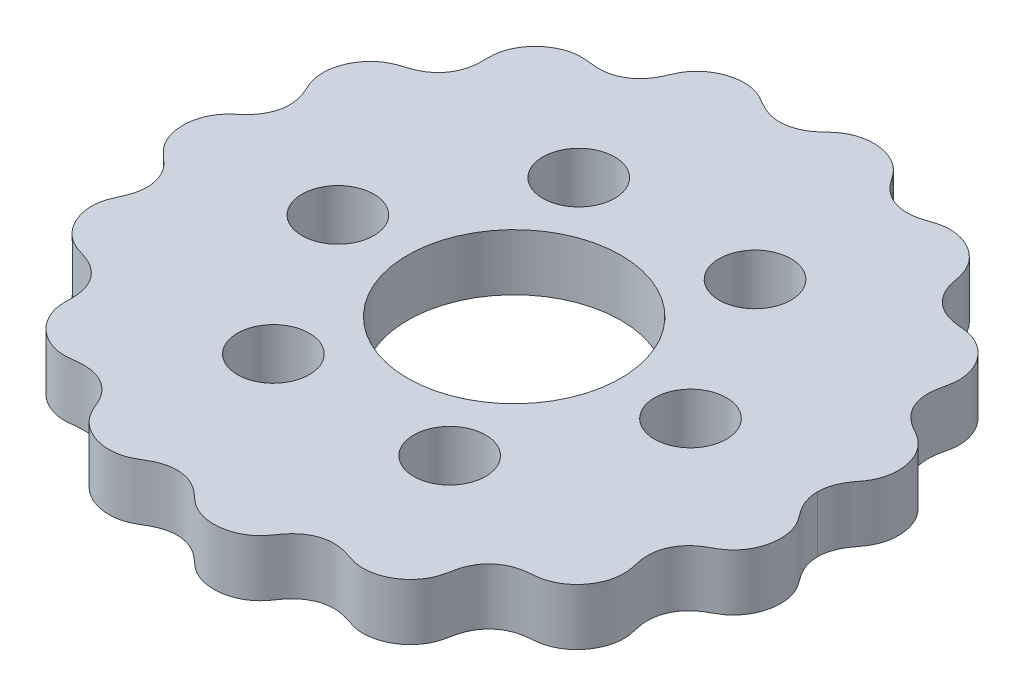
SolidWorks part; units mm, degrees
ref_plane "Alzado" through (0, 0, 0) normal (0, 0, 1) x (1, 0, 0)
ref_plane "Planta" through (0, 0, 0) normal (0, 1, 0) x (1, 0, 0)
ref_plane "Vista lateral" through (0, 0, 0) normal (1, 0, 0) x (0, 0, -1)
sketch "Croquis1" plane through (0, 0, 0) normal (0, 1, 0) x (1, 0, 0)
  line L1 (-23.5, 0) -> (21.5, 0) construction
  circle A8 centre (0, 0) radius 12.5 construction
  circle A9 centre (12.5, 0) radius 2.55
  circle A10 centre (6.25, -10.8253) radius 2.55
  circle A11 centre (-6.25, -10.8253) radius 2.55
  circle A12 centre (-12.5, 0) radius 2.55
  circle A13 centre (-6.25, 10.8253) radius 2.55
  circle A14 centre (6.25, 10.8253) radius 2.55
  circle A15 centre (0, 0) radius 7.56
  spline S0 degree 4 poles (22.3938, 6.206) (22.5098, 6.0505) (22.7166, 5.7207) (22.9456, 5.1865) (23.0698, 4.5223) (23.0708, 3.9491) (22.995, 3.4431) (22.8861, 3.0677) (22.7402, 2.7346) (22.5701, 2.4451) (22.4166, 2.2248) (22.255, 2.0106) (22.0968, 1.7938) (21.9608, 1.5854) (21.8481, 1.3858) (21.7364, 1.1545) (21.6505, 0.933) (21.5836, 0.7054) (21.5367, 0.4716) (21.5147, 0.3126) (21.5037, 0.1561) (21.4997, 0.0354) (21.4998, -0.0402) (21.5033, -0.1416) (21.5104, -0.2506) (21.521, -0.3535) (21.5352, -0.4522) (21.5572, -0.575) (21.5906, -0.7229) (21.6393, -0.8925) (21.7079, -1.082) (21.7887, -1.2667) (21.8884, -1.4605) (22.0086, -1.6616) (22.1498, -1.8685) (22.3094, -2.0824) (22.4687, -2.2964) (22.6163, -2.5189) (22.7773, -2.8114) (22.9505, -3.2395) (23.0755, -3.8173) (23.0785, -4.5347) (22.9117, -5.2906) (22.61, -5.9374) (22.2185, -6.4567) (21.7772, -6.8519) (21.3209, -7.1251) (20.8, -7.4026) (20.2753, -7.7948) (19.8063, -8.3446) (19.475, -9.0614) (19.3598, -9.7832) (19.4098, -10.4522) (19.5346, -10.9747) (19.6222, -11.3739) (19.6633, -11.7809) (19.6552, -12.251) (19.5391, -12.8416) (19.2523, -13.5076) (18.7937, -14.1364) (18.2622, -14.6034) (17.7101, -14.9167) (17.1699, -15.1) (16.67, -15.1754) (16.1916, -15.2048) (15.7411, -15.2785) (15.3268, -15.3998) (14.9543, -15.5661) (14.5264, -15.8332) (14.0827, -16.2428) (13.7242, -16.7761) (13.514, -17.344) (13.4123, -17.8049) (13.3351, -18.2081) (13.2359, -18.6074) (13.025, -19.1081) (12.6416, -19.6627) (12.1028, -20.1652) (11.4122, -20.5639) (10.7076, -20.7793) (10.0356, -20.834) (9.4966, -20.7664) (9.1011, -20.6526) (8.7134, -20.5178) (8.2633, -20.3754) (7.6664, -20.2735) (7.0253, -20.3174) (6.4487, -20.4968) (6.0035, -20.7338) (5.6732, -20.9733) (5.361, -21.2715) (5.0719, -21.6247) (4.8073, -22.0244) (4.4921, -22.4196) (4.0632, -22.7958) (3.5158, -23.1172) (2.8456, -23.344) (2.0718, -23.4267) (1.3515, -23.3422) (0.7822, -23.1473) (0.3707, -22.9196) (0.0947, -22.7199) (-0.1125, -22.543) (-0.3613, -22.3108) (-0.71, -21.9972) (-1.2072, -21.6575) (-1.8903, -21.3967) (-2.6764, -21.325) (-3.3872, -21.4564) (-3.9891, -21.7146) (-4.49, -22.027) (-4.9546, -22.2856) (-5.5176, -22.4702) (-6.163, -22.5495) (-6.8743, -22.4875) (-7.6119, -22.2539) (-8.2323, -21.8928) (-8.7188, -21.4502) (-9.0744, -20.9697) (-9.3045, -20.4864) (-9.5278, -19.9281) (-9.8701, -19.3468) (-10.3865, -18.8074) (-11.0945, -18.3987) (-11.8197, -18.2212) (-12.4943, -18.2154) (-13.0895, -18.3011) (-13.623, -18.3435) (-14.217, -18.2758) (-14.8436, -18.0758) (-15.4665, -17.719) (-16.0376, -17.197) (-16.447, -16.612) (-16.701, -16.0135) (-16.8226, -15.4336) (-16.8309, -14.902) (-16.8108, -14.312) (-16.8881, -13.6616) (-17.1298, -12.9803) (-17.5849, -12.3353) (-18.1524, -11.8742) (-18.6951, -11.6135) (-19.1411, -11.4683) (-19.4666, -11.3689) (-19.7233, -11.2779) (-20.0342, -11.1388) (-20.4373, -10.8962) (-20.8907, -10.5007) (-21.3241, -9.9191) (-21.6393, -9.2077) (-21.778, -8.5138) (-21.7733, -7.8791) (-21.6621, -7.3195) (-21.4771, -6.849) (-21.2186, -6.3289) (-21.0011, -5.7035) (-20.9214, -4.968) (-21.0454, -4.2657) (-21.2856, -3.7121) (-21.5436, -3.3243) (-21.7592, -3.0674) (-21.974, -2.8515) (-22.1775, -2.6683) (-22.3844, -2.489) (-22.5845, -2.3019) (-22.7693, -2.0995) (-22.9352, -1.8813) (-23.0967, -1.6229) (-23.2446, -1.3222) (-23.3437, -1.0477) (-23.4069, -0.8089) (-23.4413, -0.6387) (-23.4581, -0.5412) (-23.4757, -0.42) (-23.4911, -0.2795) (-23.5008, -0.0674) (-23.501, 0.0617) (-23.4905, 0.2958) (-23.4696, 0.4722) (-23.4384, 0.6634) (-23.3968, 0.8485) (-23.3447, 1.0319) (-23.2823, 1.2119) (-23.2033, 1.4023) (-23.1053, 1.6016) (-22.952, 1.8603) (-22.7243, 2.166) (-22.4073, 2.4773) (-22.0362, 2.7842) (-21.7134, 3.1099) (-21.3864, 3.5349) (-21.0986, 4.0919) (-20.9508, 4.7107) (-20.9589, 5.3479) (-21.0451, 5.768) (-21.1059, 5.9731) (-21.1402, 6.0744) knots 0 0 0 0 0 0.008384 0.016767 0.0249 0.028966 0.033032 0.038829 0.041728 0.044627 0.047525 0.050424 0.053322 0.056221 0.05827 0.060319 0.064418 0.066467 0.068516 0.070566 0.07159 0.072615 0.073703 0.074791 0.075879 0.076967 0.078055 0.079143 0.081319 0.083495 0.085672 0.087848 0.090024 0.092906 0.095787 0.098669 0.101551 0.104433 0.107315 0.113078 0.12144 0.129802 0.138039 0.146276 0.152005 0.157733 0.163462 0.169191 0.177517 0.185843 0.194348 0.202854 0.208734 0.214615 0.217555 0.220495 0.226376 0.23487 0.243365 0.251552 0.25974 0.265182 0.270624 0.276066 0.281508 0.285899 0.29029 0.294681 0.299071 0.307626 0.316181 0.322096 0.325053 0.328011 0.333925 0.33984 0.348384 0.356927 0.365471 0.374015 0.37993 0.385844 0.388802 0.391759 0.397674 0.406229 0.414784 0.419174 0.423565 0.427956 0.432347 0.437789 0.443231 0.448673 0.454115 0.462303 0.47049 0.478985 0.487479 0.49336 0.4963 0.49924 0.502181 0.505121 0.511001 0.519507 0.528012 0.536338 0.544664 0.550393 0.556122 0.56185 0.567579 0.575816 0.584053 0.592415 0.600777 0.60654 0.612304 0.618068 0.623831 0.632536 0.64124 0.649944 0.658649 0.664412 0.670176 0.67594 0.681703 0.690065 0.698427 0.706664 0.714901 0.72063 0.726358 0.732087 0.737816 0.746142 0.754468 0.762973 0.771479 0.777359 0.780299 0.78324 0.78618 0.78912 0.795001 0.803495 0.81199 0.820177 0.828365 0.833807 0.839249 0.844691 0.850133 0.858915 0.867696 0.876251 0.880529 0.884806 0.887763 0.890721 0.893678 0.896636 0.899593 0.90255 0.905508 0.908465 0.912737 0.917009 0.918077 0.919145 0.920213 0.921281 0.923416 0.925552 0.927609 0.929666 0.931723 0.93378 0.935836 0.937893 0.93995 0.942007 0.944741 0.947474 0.952942 0.95841 0.963877 0.968289 0.972701 0.981525 0.990762 0.995381 1 1 1 1 1 construction
  spline S1 degree 4 poles (21.5, 0) (21.5, -0.0215) (21.5006, -0.0644) (21.5033, -0.1416) (21.5104, -0.2506) (21.521, -0.3535) (21.5352, -0.4522) (21.5572, -0.575) (21.5906, -0.7229) (21.6393, -0.8925) (21.7079, -1.082) (21.7887, -1.2667) (21.8884, -1.4605) (22.0086, -1.6616) (22.1498, -1.8685) (22.3094, -2.0824) (22.4687, -2.2964) (22.6163, -2.5189) (22.7773, -2.8114) (22.9505, -3.2395) (23.0755, -3.8173) (23.0785, -4.5347) (22.9117, -5.2906) (22.61, -5.9374) (22.2185, -6.4567) (21.7772, -6.8519) (21.3209, -7.1251) (20.8, -7.4026) (20.2753, -7.7948) (19.8063, -8.3446) (19.475, -9.0614) (19.3598, -9.7832) (19.4098, -10.4522) (19.5346, -10.9747) (19.6222, -11.3739) (19.6633, -11.7809) (19.6552, -12.251) (19.5391, -12.8416) (19.2523, -13.5076) (18.7937, -14.1364) (18.2622, -14.6034) (17.7101, -14.9167) (17.1699, -15.1) (16.67, -15.1754) (16.1916, -15.2048) (15.7411, -15.2785) (15.3268, -15.3998) (14.9543, -15.5661) (14.5264, -15.8332) (14.0827, -16.2428) (13.7242, -16.7761) (13.514, -17.344) (13.4123, -17.8049) (13.3351, -18.2081) (13.2359, -18.6074) (13.025, -19.1081) (12.6416, -19.6627) (12.1028, -20.1652) (11.4122, -20.5639) (10.7076, -20.7793) (10.0356, -20.834) (9.4966, -20.7664) (9.1011, -20.6526) (8.7134, -20.5178) (8.2633, -20.3754) (7.6664, -20.2735) (7.0253, -20.3174) (6.4487, -20.4968) (6.0035, -20.7338) (5.6732, -20.9733) (5.361, -21.2715) (5.0719, -21.6247) (4.8073, -22.0244) (4.4921, -22.4196) (4.0632, -22.7958) (3.5158, -23.1172) (2.8456, -23.344) (2.0718, -23.4267) (1.3515, -23.3422) (0.7822, -23.1473) (0.3707, -22.9196) (0.0947, -22.7199) (-0.1125, -22.543) (-0.3613, -22.3108) (-0.71, -21.9972) (-1.2072, -21.6575) (-1.8903, -21.3967) (-2.6764, -21.325) (-3.3872, -21.4564) (-3.9891, -21.7146) (-4.49, -22.027) (-4.9546, -22.2856) (-5.5176, -22.4702) (-6.163, -22.5495) (-6.8743, -22.4875) (-7.6119, -22.2539) (-8.2323, -21.8928) (-8.7188, -21.4502) (-9.0744, -20.9697) (-9.3045, -20.4864) (-9.5278, -19.9281) (-9.8701, -19.3468) (-10.3865, -18.8074) (-11.0945, -18.3987) (-11.8197, -18.2212) (-12.4943, -18.2154) (-13.0895, -18.3011) (-13.623, -18.3435) (-14.217, -18.2758) (-14.8436, -18.0758) (-15.4665, -17.719) (-16.0376, -17.197) (-16.447, -16.612) (-16.701, -16.0135) (-16.8226, -15.4336) (-16.8309, -14.902) (-16.8108, -14.312) (-16.8881, -13.6616) (-17.1298, -12.9803) (-17.5849, -12.3353) (-18.1524, -11.8742) (-18.6951, -11.6135) (-19.1411, -11.4683) (-19.4666, -11.3689) (-19.7233, -11.2779) (-20.0342, -11.1388) (-20.4373, -10.8962) (-20.8907, -10.5007) (-21.3241, -9.9191) (-21.6393, -9.2077) (-21.778, -8.5138) (-21.7733, -7.8791) (-21.6621, -7.3195) (-21.4771, -6.849) (-21.2186, -6.3289) (-21.0011, -5.7035) (-20.9214, -4.968) (-21.0454, -4.2657) (-21.2856, -3.7121) (-21.5436, -3.3243) (-21.7592, -3.0674) (-21.974, -2.8515) (-22.1775, -2.6683) (-22.3844, -2.489) (-22.5845, -2.3019) (-22.7693, -2.0995) (-22.9352, -1.8813) (-23.0967, -1.6229) (-23.2446, -1.3222) (-23.3437, -1.0477) (-23.4069, -0.8089) (-23.4413, -0.6387) (-23.4581, -0.5412) (-23.4757, -0.42) (-23.4911, -0.2795) (-23.4981, -0.1264) (-23.5, -0.0422) (-23.5, 0) knots 0.072615 0.072615 0.072615 0.072615 0.072615 0.073703 0.074791 0.075879 0.076967 0.078055 0.079143 0.081319 0.083495 0.085672 0.087848 0.090024 0.092906 0.095787 0.098669 0.101551 0.104433 0.107315 0.113078 0.12144 0.129802 0.138039 0.146276 0.152005 0.157733 0.163462 0.169191 0.177517 0.185843 0.194348 0.202854 0.208734 0.214615 0.217555 0.220495 0.226376 0.23487 0.243365 0.251552 0.25974 0.265182 0.270624 0.276066 0.281508 0.285899 0.29029 0.294681 0.299071 0.307626 0.316181 0.322096 0.325053 0.328011 0.333925 0.33984 0.348384 0.356927 0.365471 0.374015 0.37993 0.385844 0.388802 0.391759 0.397674 0.406229 0.414784 0.419174 0.423565 0.427956 0.432347 0.437789 0.443231 0.448673 0.454115 0.462303 0.47049 0.478985 0.487479 0.49336 0.4963 0.49924 0.502181 0.505121 0.511001 0.519507 0.528012 0.536338 0.544664 0.550393 0.556122 0.56185 0.567579 0.575816 0.584053 0.592415 0.600777 0.60654 0.612304 0.618068 0.623831 0.632536 0.64124 0.649944 0.658649 0.664412 0.670176 0.67594 0.681703 0.690065 0.698427 0.706664 0.714901 0.72063 0.726358 0.732087 0.737816 0.746142 0.754468 0.762973 0.771479 0.777359 0.780299 0.78324 0.78618 0.78912 0.795001 0.803495 0.81199 0.820177 0.828365 0.833807 0.839249 0.844691 0.850133 0.858915 0.867696 0.876251 0.880529 0.884806 0.887763 0.890721 0.893678 0.896636 0.899593 0.90255 0.905508 0.908465 0.912737 0.917009 0.918077 0.919145 0.920213 0.921281 0.923416 0.925552 0.925552 0.925552 0.925552 0.925552
  spline S2 degree 4 poles (21.5, 0) (21.5, 0.0215) (21.5006, 0.0644) (21.5033, 0.1416) (21.5104, 0.2506) (21.521, 0.3535) (21.5352, 0.4522) (21.5572, 0.575) (21.5906, 0.7229) (21.6393, 0.8925) (21.7079, 1.082) (21.7887, 1.2667) (21.8884, 1.4605) (22.0086, 1.6616) (22.1498, 1.8685) (22.3094, 2.0824) (22.4687, 2.2964) (22.6163, 2.5189) (22.7773, 2.8114) (22.9505, 3.2395) (23.0755, 3.8173) (23.0785, 4.5347) (22.9117, 5.2906) (22.61, 5.9374) (22.2185, 6.4567) (21.7772, 6.8519) (21.3209, 7.1251) (20.8, 7.4026) (20.2753, 7.7948) (19.8063, 8.3446) (19.475, 9.0614) (19.3598, 9.7832) (19.4098, 10.4522) (19.5346, 10.9747) (19.6222, 11.3739) (19.6633, 11.7809) (19.6552, 12.251) (19.5391, 12.8416) (19.2523, 13.5076) (18.7937, 14.1364) (18.2622, 14.6034) (17.7101, 14.9167) (17.1699, 15.1) (16.67, 15.1754) (16.1916, 15.2048) (15.7411, 15.2785) (15.3268, 15.3998) (14.9543, 15.5661) (14.5264, 15.8332) (14.0827, 16.2428) (13.7242, 16.7761) (13.514, 17.344) (13.4123, 17.8049) (13.3351, 18.2081) (13.2359, 18.6074) (13.025, 19.1081) (12.6416, 19.6627) (12.1028, 20.1652) (11.4122, 20.5639) (10.7076, 20.7793) (10.0356, 20.834) (9.4966, 20.7664) (9.1011, 20.6526) (8.7134, 20.5178) (8.2633, 20.3754) (7.6664, 20.2735) (7.0253, 20.3174) (6.4487, 20.4968) (6.0035, 20.7338) (5.6732, 20.9733) (5.361, 21.2715) (5.0719, 21.6247) (4.8073, 22.0244) (4.4921, 22.4196) (4.0632, 22.7958) (3.5158, 23.1172) (2.8456, 23.344) (2.0718, 23.4267) (1.3515, 23.3422) (0.7822, 23.1473) (0.3707, 22.9196) (0.0947, 22.7199) (-0.1125, 22.543) (-0.3613, 22.3108) (-0.71, 21.9972) (-1.2072, 21.6575) (-1.8903, 21.3967) (-2.6764, 21.325) (-3.3872, 21.4564) (-3.9891, 21.7146) (-4.49, 22.027) (-4.9546, 22.2856) (-5.5176, 22.4702) (-6.163, 22.5495) (-6.8743, 22.4875) (-7.6119, 22.2539) (-8.2323, 21.8928) (-8.7188, 21.4502) (-9.0744, 20.9697) (-9.3045, 20.4864) (-9.5278, 19.9281) (-9.8701, 19.3468) (-10.3865, 18.8074) (-11.0945, 18.3987) (-11.8197, 18.2212) (-12.4943, 18.2154) (-13.0895, 18.3011) (-13.623, 18.3435) (-14.217, 18.2758) (-14.8436, 18.0758) (-15.4665, 17.719) (-16.0376, 17.197) (-16.447, 16.612) (-16.701, 16.0135) (-16.8226, 15.4336) (-16.8309, 14.902) (-16.8108, 14.312) (-16.8881, 13.6616) (-17.1298, 12.9803) (-17.5849, 12.3353) (-18.1524, 11.8742) (-18.6951, 11.6135) (-19.1411, 11.4683) (-19.4666, 11.3689) (-19.7233, 11.2779) (-20.0342, 11.1388) (-20.4373, 10.8962) (-20.8907, 10.5007) (-21.3241, 9.9191) (-21.6393, 9.2077) (-21.778, 8.5138) (-21.7733, 7.8791) (-21.6621, 7.3195) (-21.4771, 6.849) (-21.2186, 6.3289) (-21.0011, 5.7035) (-20.9214, 4.968) (-21.0454, 4.2657) (-21.2856, 3.7121) (-21.5436, 3.3243) (-21.7592, 3.0674) (-21.974, 2.8515) (-22.1775, 2.6683) (-22.3844, 2.489) (-22.5845, 2.3019) (-22.7693, 2.0995) (-22.9352, 1.8813) (-23.0967, 1.6229) (-23.2446, 1.3222) (-23.3437, 1.0477) (-23.4069, 0.8089) (-23.4413, 0.6387) (-23.4581, 0.5412) (-23.4757, 0.42) (-23.4911, 0.2795) (-23.4981, 0.1264) (-23.5, 0.0422) (-23.5, 0) knots 0.072615 0.072615 0.072615 0.072615 0.072615 0.073703 0.074791 0.075879 0.076967 0.078055 0.079143 0.081319 0.083495 0.085672 0.087848 0.090024 0.092906 0.095787 0.098669 0.101551 0.104433 0.107315 0.113078 0.12144 0.129802 0.138039 0.146276 0.152005 0.157733 0.163462 0.169191 0.177517 0.185843 0.194348 0.202854 0.208734 0.214615 0.217555 0.220495 0.226376 0.23487 0.243365 0.251552 0.25974 0.265182 0.270624 0.276066 0.281508 0.285899 0.29029 0.294681 0.299071 0.307626 0.316181 0.322096 0.325053 0.328011 0.333925 0.33984 0.348384 0.356927 0.365471 0.374015 0.37993 0.385844 0.388802 0.391759 0.397674 0.406229 0.414784 0.419174 0.423565 0.427956 0.432347 0.437789 0.443231 0.448673 0.454115 0.462303 0.47049 0.478985 0.487479 0.49336 0.4963 0.49924 0.502181 0.505121 0.511001 0.519507 0.528012 0.536338 0.544664 0.550393 0.556122 0.56185 0.567579 0.575816 0.584053 0.592415 0.600777 0.60654 0.612304 0.618068 0.623831 0.632536 0.64124 0.649944 0.658649 0.664412 0.670176 0.67594 0.681703 0.690065 0.698427 0.706664 0.714901 0.72063 0.726358 0.732087 0.737816 0.746142 0.754468 0.762973 0.771479 0.777359 0.780299 0.78324 0.78618 0.78912 0.795001 0.803495 0.81199 0.820177 0.828365 0.833807 0.839249 0.844691 0.850133 0.858915 0.867696 0.876251 0.880529 0.884806 0.887763 0.890721 0.893678 0.896636 0.899593 0.90255 0.905508 0.908465 0.912737 0.917009 0.918077 0.919145 0.920213 0.921281 0.923416 0.925552 0.925552 0.925552 0.925552 0.925552
  point P22 (0, 0)
  dimension "D1" = 5.1
  dimension "D2" = 25
  dimension "D3" = 15.12
extrude "Saliente-Extruir1" add sketch "Croquis1" along normal mid plane 4
